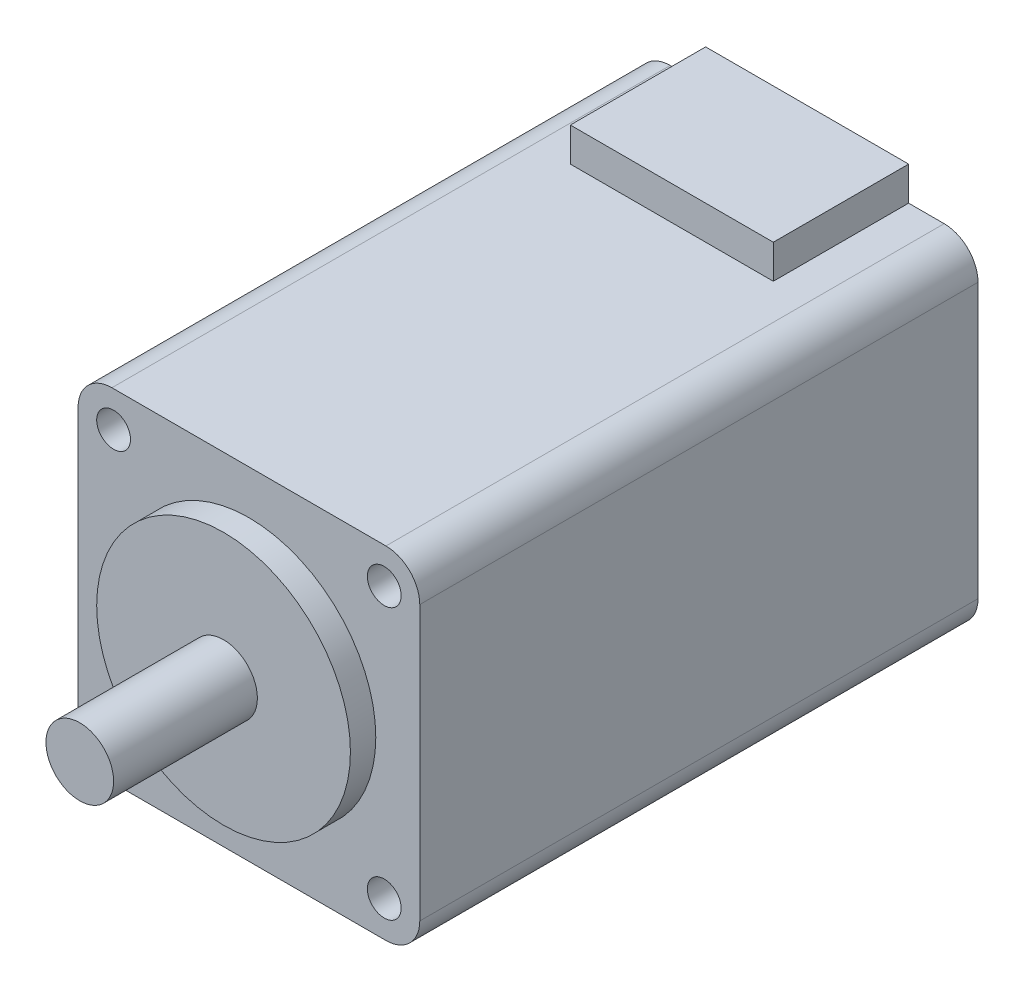
SolidWorks part; units mm, degrees
material "Malleable Cast Iron"
ref_plane "Front Plane" through (0, 0, 0) normal (0, 0, 1) x (1, 0, 0)
ref_plane "Top Plane" through (0, 0, 0) normal (0, 1, 0) x (1, 0, 0)
ref_plane "Right Plane" through (0, 0, 0) normal (1, 0, 0) x (0, 0, -1)
sketch "Sketch1" plane through (0, 0, 0) normal (0, 0, 1) x (1, 0, 0)
  line L1 (-8.1, -10.1) -> (8.1, -10.1)
  line L2 (-10.1, -8.1) -> (-10.1, 8.1)
  line L3 (-8.1, 10.1) -> (8.1, 10.1)
  line L4 (10.1, -8.1) -> (10.1, 8.1)
  line L5 (-10.1, -10.1) -> (10.1, 10.1) construction
  line L6 (-10.1, 10.1) -> (10.1, -10.1) construction
  arc A0 (-10.1, 8.1) -> (-8.1, 10.1) centre (-8.1, 8.1) cw
  arc A1 (8.1, 10.1) -> (10.1, 8.1) centre (8.1, 8.1) cw
  arc A2 (8.1, -10.1) -> (10.1, -8.1) centre (8.1, -8.1) ccw
  arc A3 (-8.1, -10.1) -> (-10.1, -8.1) centre (-8.1, -8.1) cw
  point P0 (0, 0)
  dimension "D3" = 2
  dimension "D4" = 2
  dimension "D1" = 20.2
  dimension "D2" = 20.2
extrude "Boss-Extrude1" add sketch "Sketch1" against normal blind 33
sketch "Sketch2" plane through (0, 0, 0) normal (0, 0, 1) x (1, 0, 0)
  line L0 (0, -8) -> (0, 8) construction
  line L1 (-8, 0) -> (8, 0) construction
  line L2 (-8, 0) -> (-8, 8) construction
  line L3 (0, 8) -> (-8, 8) construction
  line L4 (-8, -8) -> (-8, 8) construction
  line L5 (8.1, 10.1) -> (-8.1, 10.1) construction
  circle A0 centre (-8, 8) radius 1
  circle A1 centre (8, 8) radius 1
  circle A2 centre (8, -8) radius 1
  circle A3 centre (-8, -8) radius 1
  point P4 (0, 0)
  point P8 (0, 0)
  dimension "D3" = 2
  dimension "D1" = 16
  dimension "D2" = 16
  dimension "D6" = 16
  dimension "D7" = 16
  dimension "D4" = 2
  dimension "D5" = 2
extrude "Cut-Extrude1" cut sketch "Sketch2" against normal blind 3.5
sketch "Sketch3" plane through (0, 0, -33) normal (0, 0, -1) x (-1, 0, 0)
  line L0 (0, 0) -> (0, 10.1) construction
  line L1 (-8.1, 10.1) -> (8.1, 10.1) construction
  line L2 (-6, 10.1) -> (6, 10.1) construction
  line L8 (-6, 10.1) -> (6, 10.1)
  line L9 (-6, 10.1) -> (-6, 12.1)
  line L10 (-6, 12.1) -> (6, 12.1)
  line L11 (6, 10.1) -> (6, 12.1)
  point P8 (0, 10.1)
  dimension "D1" = 12
  dimension "D2" = 2
extrude "Boss-Extrude2" add sketch "Sketch3" against normal blind 8
sketch "Sketch4" plane through (0, 0, 0) normal (0, 0, 1) x (1, 0, 0)
  circle A0 centre (0, 0) radius 7.5
  dimension "D1" = 15
extrude "Boss-Extrude3" add sketch "Sketch4" along normal blind 1.5
sketch "Sketch5" plane through (0, 0, 1.5) normal (0, 0, 1) x (1, 0, 0)
  circle A0 centre (0, 0) radius 2
  dimension "D1" = 4
extrude "Boss-Extrude4" add sketch "Sketch5" along normal blind 8.5
